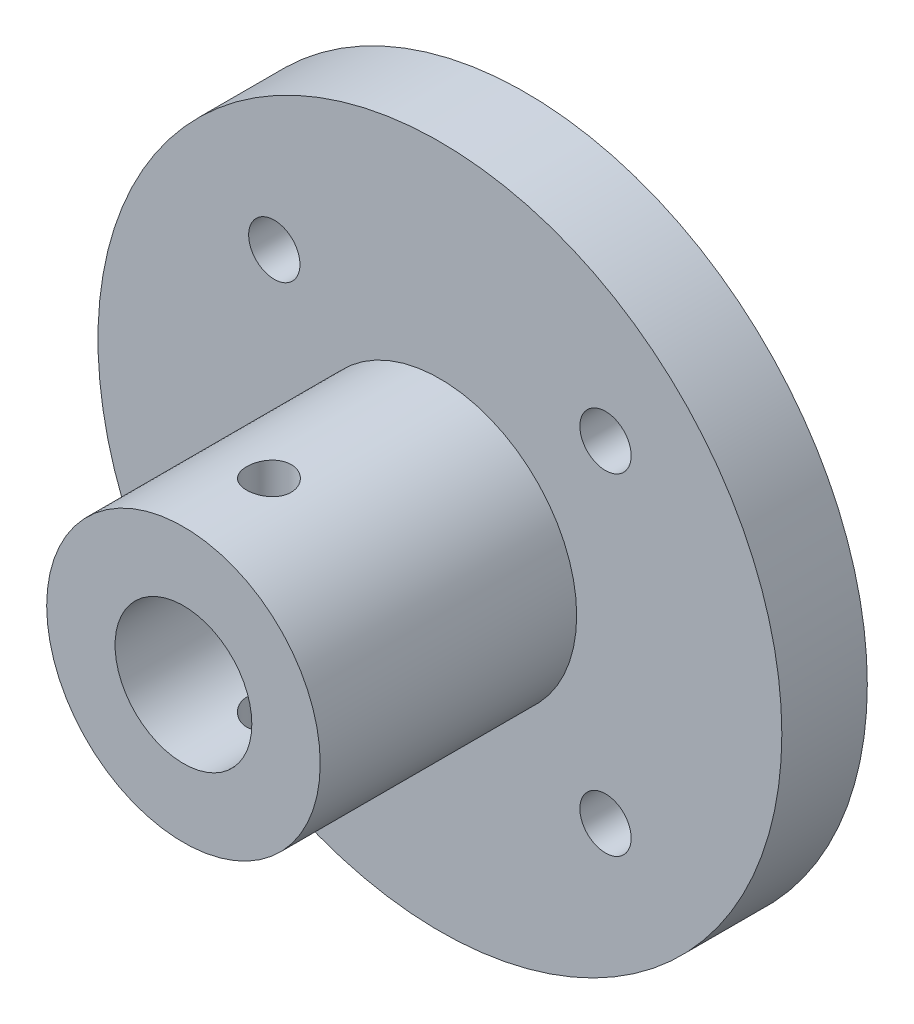
SolidWorks part; units mm, degrees
ref_plane "Front Plane" through (0, 0, 0) normal (0, 0, 1) x (1, 0, 0)
ref_plane "Top Plane" through (0, 0, 0) normal (0, 1, 0) x (1, 0, 0)
ref_plane "Right Plane" through (0, 0, 0) normal (1, 0, 0) x (0, 0, -1)
sketch "Sketch1" plane through (0, 0, 0) normal (0, 0, 1) x (1, 0, 0)
  line L0 (0, 0) -> (0, 20) construction
  line L1 (0, 20) -> (0, 0) construction
  line L2 (0, 0) -> (-20, 0) construction
  line L3 (0, 0) -> (-14.1421, 14.1421) construction
  circle A0 centre (0, 0) radius 4
  circle A1 centre (0, 0) radius 20
  circle A2 centre (-9.6862, 9.6862) radius 1.5
  circle A3 centre (9.6862, 9.6862) radius 1.5
  circle A4 centre (9.6862, -9.6862) radius 1.5
  circle A5 centre (-9.6862, -9.6862) radius 1.5
  dimension "D1" = 8
  dimension "D2" = 40
  dimension "D3" = 3
extrude "Boss-Extrude1" add sketch "Sketch1" along normal blind 5
sketch "Sketch2" plane through (0, 0, 5) normal (0, 0, 1) x (1, 0, 0)
  circle A1 centre (0, 0) radius 4
  circle A2 centre (0, 0) radius 8
  dimension "D1" = 16
  dimension "D2" = 8
extrude "Boss-Extrude2" add sketch "Sketch2" along normal blind 15
sketch "Sketch3" plane through (0, 0, 0) normal (0, 1, 0) x (1, 0, 0)
  line L0 (0, -5) -> (0, -22.7914) construction
  line L1 (-8, -5) -> (8, -5) construction
  line L2 (-8, -20) -> (11.7824, -20) construction
  circle A0 centre (0, -15) radius 1.3019
  dimension "D1" = 5
extrude "Cut-Extrude1" cut sketch "Sketch3" against normal through all both and the other way through all
